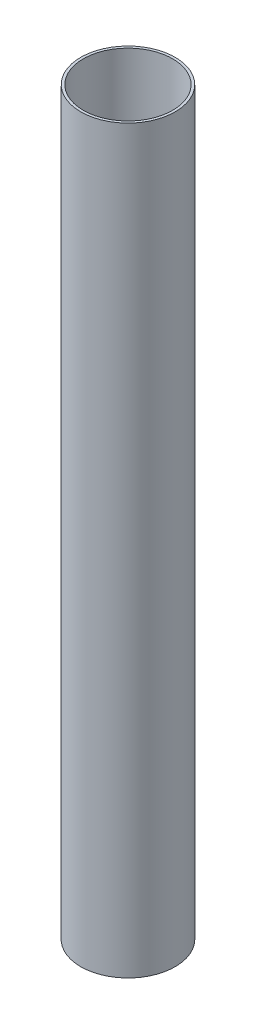
SolidWorks part; units mm, degrees
ref_plane "Front Plane" through (0, 0, 0) normal (0, 0, 1) x (1, 0, 0)
ref_plane "Top Plane" through (0, 0, 0) normal (0, 1, 0) x (1, 0, 0)
ref_plane "Right Plane" through (0, 0, 0) normal (1, 0, 0) x (0, 0, -1)
sketch "Sketch1" plane through (0, 0, 0) normal (0, 1, 0) x (1, 0, 0)
  circle A0 centre (0, 0) radius 46.99
  circle A1 centre (0, 0) radius 44.45
sketch3d "3DSketch1"
  line L0 (0, 0, 0) -> (0, 736.6, 0)
sweep "Sweep1" add profiles "Sketch1" path "3DSketch1"
